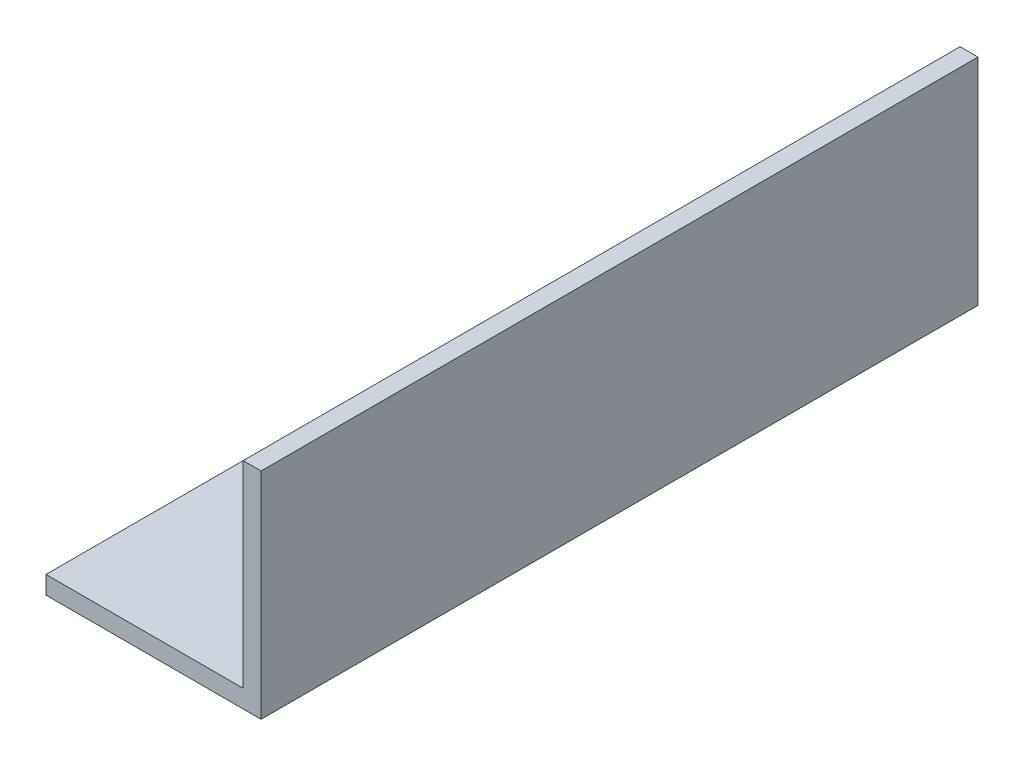
SolidWorks part; units mm, degrees
ref_plane "Front Plane" through (0, 0, 0) normal (0, 0, 1) x (1, 0, 0)
ref_plane "Top Plane" through (0, 0, 0) normal (0, 1, 0) x (1, 0, 0)
ref_plane "Right Plane" through (0, 0, 0) normal (1, 0, 0) x (0, 0, -1)
sketch "Sketch1" plane through (0, 0, 0) normal (0, 0, 1) x (1, 0, 0)
  line L1 (0, 0) -> (38.1, 0)
  line L2 (0, 0) -> (0, 38.1)
  line L3 (0, 38.1) -> (38.1, 38.1)
  line L4 (38.1, 0) -> (38.1, 38.1)
  dimension "D1" = 38.1
  dimension "D2" = 38.1
extrude "Boss-Extrude1" add sketch "Sketch1" along normal blind 127
sketch "Sketch3" plane through (0, 0, 127) normal (0, 0, 1) x (1, 0, 0)
  line L1 (0, 38.1) -> (34.925, 38.1)
  line L2 (0, 38.1) -> (0, 3.175)
  line L3 (0, 3.175) -> (34.925, 3.175)
  line L4 (34.925, 38.1) -> (34.925, 3.175)
  dimension "D1" = 34.925
  dimension "D2" = 34.925
extrude "Cut-Extrude1" cut sketch "Sketch3" against normal blind 127
